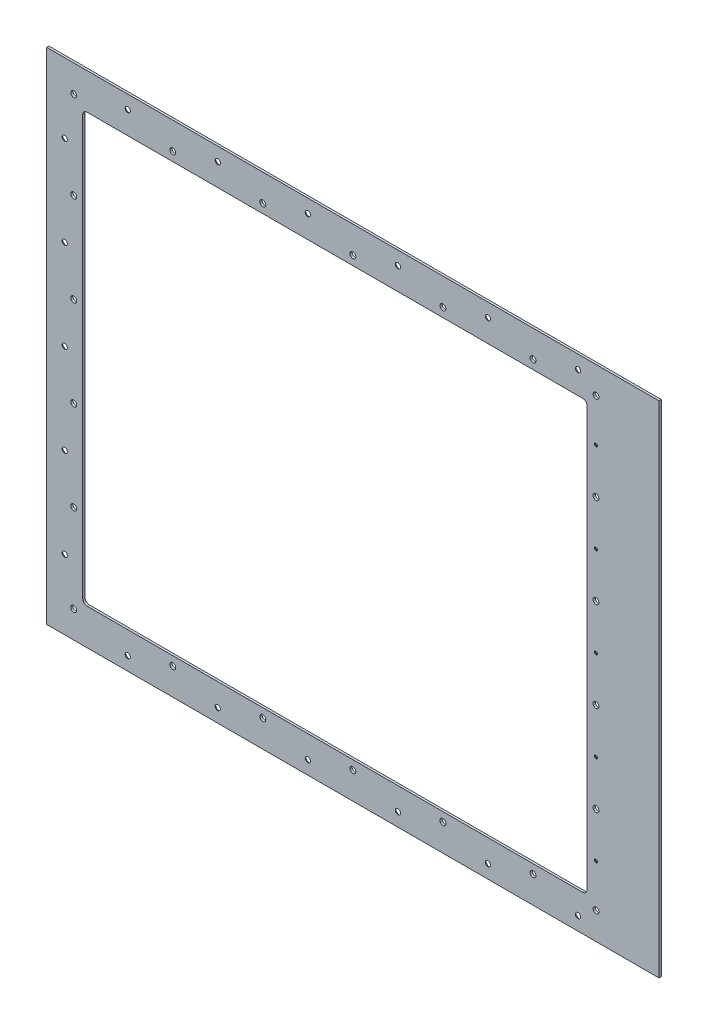
SolidWorks part; units mm, degrees
material "6061-T6 (SS)"
ref_plane "Front" through (0, 0, 0) normal (0, 0, 1) x (1, 0, 0)
ref_plane "Top" through (0, 0, 0) normal (0, 1, 0) x (1, 0, 0)
ref_plane "Right" through (0, 0, 0) normal (1, 0, 0) x (0, 0, -1)
sketch "Sketch1" plane through (0, 0, 0) normal (0, 0, 1) x (1, 0, 0)
  line L1 (0, 0) -> (863.6, 0)
  line L2 (0, 0) -> (0, 704.85)
  line L3 (0, 704.85) -> (863.6, 704.85)
  line L4 (863.6, 0) -> (863.6, 704.85)
  dimension "D1" = 704.85
  dimension "D2" = 863.6
extrude "Boss-Extrude1" add sketch "Sketch1" along normal blind 3.175
sketch "Sketch2" plane through (0, 0, 3.175) normal (0, 0, 1) x (1, 0, 0)
  line L0 (863.6, 704.85) -> (0, 704.85) construction
  line L1 (50.8, 50.8) -> (762, 50.8)
  line L2 (50.8, 50.8) -> (50.8, 654.05)
  line L3 (50.8, 654.05) -> (762, 654.05)
  line L4 (762, 50.8) -> (762, 654.05)
  line L5 (863.6, 0) -> (863.6, 704.85) construction
  line L6 (0, 0) -> (863.6, 0) construction
  line L7 (0, 704.85) -> (0, 0) construction
  dimension "D1" = 50.8
  dimension "D2" = 101.6
  dimension "D3" = 50.8
  dimension "D4" = 50.8
extrude "Cut-Extrude1" cut sketch "Sketch2" against normal through all
hole_wizard "CSK for 1/4 Flat Head Machine Screw2" positions "Sketch11" profile "Sketch12" countersink size "1/4" standard "ANSI Inch" end condition through all
sketch "Sketch11" plane through (0, 0, 0) normal (0, 0, -1) x (-1, 0, 0)
  line L0 (0, 0) -> (-863.6, 0) construction
  line L1 (0, 704.85) -> (0, 0) construction
  point P0 (-114.3, 19.05)
  dimension "D1" = 19.05
  dimension "D2" = 114.3
sketch "Sketch12" plane through (114.3, 19.05, 0) normal (1, 0, 0) x (0, 1, 0)
  line L0 (0, 0) -> (0, 3.175)
  line L1 (0, 3.175) -> (3.3782, 3.175)
  line L2 (3.3782, 3.175) -> (3.3782, 3.5209)
  line L3 (3.3782, 3.5209) -> (6.4389, 0)
  line L5 (6.4389, 0) -> (0, 0)
  line L6 (-3.3782, 3.5209) -> (-6.4389, 0) construction
  line L11 (0, -6.35) -> (0, 107.95) construction
  dimension "Thru Hole Dia." = 6.7564
  dimension "Thru Hole Depth" = 3.175
  dimension "Near C'Sink Dia." = 12.8778
  dimension "Near C'Sink Angle" = 82
pattern_linear "LPattern4" count 6 spacing 127 along (1, 0, 0) count 2 spacing 666.75 along (0, 1, 0) of "CSK for 1/4 Flat Head Machine Screw2"
hole_wizard "CSK for 1/4 Flat Head Machine Screw3" positions "Sketch13" profile "Sketch14" countersink size "1/4" standard "ANSI Inch" end condition through all
sketch "Sketch13" plane through (0, 0, 0) normal (0, 0, -1) x (-1, 0, 0)
  line L0 (0, 704.85) -> (0, 0) construction
  line L1 (0, 0) -> (-863.6, 0) construction
  point P0 (-25.4, 98.425)
  dimension "D1" = 25.4
  dimension "D2" = 98.425
sketch "Sketch14" plane through (25.4, 98.425, 0) normal (1, 0, 0) x (0, 1, 0)
  line L0 (0, 0) -> (0, 3.175)
  line L1 (0, 3.175) -> (3.3782, 3.175)
  line L2 (3.3782, 3.175) -> (3.3782, 3.5209)
  line L3 (3.3782, 3.5209) -> (6.4389, 0)
  line L5 (6.4389, 0) -> (0, 0)
  line L6 (-3.3782, 3.5209) -> (-6.4389, 0) construction
  line L11 (0, -6.35) -> (0, 107.95) construction
  dimension "Thru Hole Dia." = 6.7564
  dimension "Thru Hole Depth" = 3.175
  dimension "Near C'Sink Dia." = 12.8778
  dimension "Near C'Sink Angle" = 82
pattern_linear "LPattern5" count 5 spacing 127 along (0, 1, 0) of "CSK for 1/4 Flat Head Machine Screw3"
hole_wizard "21/64 (0.32813) Diameter Hole1" positions "Sketch15" profile "Sketch16" hole size "21/64" standard "ANSI Inch" end condition through all
sketch "Sketch15" plane through (0, 0, 0) normal (0, 0, -1) x (-1, 0, 0)
  line L0 (-50.8, 50.8) -> (-762, 50.8) construction
  line L1 (-50.8, 654.05) -> (-50.8, 50.8) construction
  point P0 (-38.1, 38.1)
  dimension "D1" = 12.7
  dimension "D2" = 12.7
sketch "Sketch16" plane through (38.1, 38.1, 0) normal (1, 0, 0) x (0, 1, 0)
  line L0 (0, 0) -> (0, 3.175)
  line L1 (0, 3.175) -> (4.1673, 3.175)
  line L2 (4.1673, 3.175) -> (4.1673, 0)
  line L5 (4.1673, 0) -> (0, 0)
  line L11 (0, -6.35) -> (0, 107.95) construction
  dimension "Thru Hole Dia." = 8.3345
  dimension "Thru Hole Depth" = 3.175
pattern_linear "LPattern6" count 2 spacing 736.6 along (1, 0, 0) count 2 spacing 628.65 along (0, 1, 0) of "21/64 (0.32813) Diameter Hole1"
hole_wizard "21/64 (0.32813) Diameter Hole2" positions "Sketch17" profile "Sketch18" hole size "21/64" standard "ANSI Inch" end condition through all
sketch "Sketch17" plane through (0, 0, 0) normal (0, 0, -1) x (-1, 0, 0)
  line L0 (-50.8, 50.8) -> (-762, 50.8) construction
  line L1 (-50.8, 654.05) -> (-50.8, 50.8) construction
  point P0 (-177.8, 38.1)
  dimension "D1" = 12.7
  dimension "D2" = 127
sketch "Sketch18" plane through (177.8, 38.1, 0) normal (1, 0, 0) x (0, 1, 0)
  line L0 (0, 0) -> (0, 3.175)
  line L1 (0, 3.175) -> (4.1673, 3.175)
  line L2 (4.1673, 3.175) -> (4.1673, 0)
  line L5 (4.1673, 0) -> (0, 0)
  line L11 (0, -6.35) -> (0, 107.95) construction
  dimension "Thru Hole Dia." = 8.3345
  dimension "Thru Hole Depth" = 3.175
pattern_linear "LPattern7" count 5 spacing 127 along (1, 0, 0) count 2 spacing 628.65 along (0, 1, 0) of "21/64 (0.32813) Diameter Hole2"
hole_wizard "21/64 (0.32813) Diameter Hole3" positions "Sketch19" profile "Sketch20" hole size "21/64" standard "ANSI Inch" end condition through all
sketch "Sketch19" plane through (0, 0, 0) normal (0, 0, -1) x (-1, 0, 0)
  line L0 (-50.8, 654.05) -> (-50.8, 50.8) construction
  circle A0 centre (-38.1, 38.1) radius 4.1673 construction
  point P0 (-38.1, 161.925)
  dimension "D1" = 123.825
  dimension "D2" = 12.7
sketch "Sketch20" plane through (38.1, 161.925, 0) normal (1, 0, 0) x (0, 1, 0)
  line L0 (0, 0) -> (0, 3.175)
  line L1 (0, 3.175) -> (4.1673, 3.175)
  line L2 (4.1673, 3.175) -> (4.1673, 0)
  line L5 (4.1673, 0) -> (0, 0)
  line L11 (0, -6.35) -> (0, 107.95) construction
  dimension "Thru Hole Dia." = 8.3345
  dimension "Thru Hole Depth" = 3.175
pattern_linear "LPattern8" count 4 spacing 127 along (0, 1, 0) count 2 spacing 736.6 along (1, 0, 0) of "21/64 (0.32813) Diameter Hole3"
fillet "Fillet1" radius 6.35 4 edges at (762, 50.8, 1.5875) (50.8, 50.8, 1.5875) (50.8, 654.05, 1.5875) (762, 654.05, 1.5875)
hole_wizard "CSK for #8 Flat Head Machine Screw1" positions "Sketch21" profile "Sketch22" countersink size "#8" standard "ANSI Inch" end condition through all
sketch "Sketch21" plane through (0, 0, 0) normal (0, 0, -1) x (-1, 0, 0)
  line L0 (-762, 57.15) -> (-762, 647.7) construction
  circle A0 centre (-774.7, 415.925) radius 4.1673 construction
  point P0 (-774.7, 606.425)
  dimension "D2" = 190.5
  dimension "D1" = 12.7
sketch "Sketch22" plane through (774.7, 606.425, 0) normal (1, 0, 0) x (0, 1, 0)
  line L0 (0, 0) -> (0, 3.175)
  line L1 (0, 3.175) -> (2.2479, 3.175)
  line L2 (2.2479, 3.175) -> (2.2479, 2.2645)
  line L3 (2.2479, 2.2645) -> (4.2164, 0)
  line L5 (4.2164, 0) -> (0, 0)
  line L6 (-2.2479, 2.2645) -> (-4.2164, 0) construction
  line L11 (0, -6.35) -> (0, 107.95) construction
  dimension "Thru Hole Dia." = 4.4958
  dimension "Thru Hole Depth" = 3.175
  dimension "Near C'Sink Dia." = 8.4328
  dimension "Near C'Sink Angle" = 82
pattern_linear "LPattern9" count 5 spacing 127 along (0, -1, 0) of "CSK for #8 Flat Head Machine Screw1"
